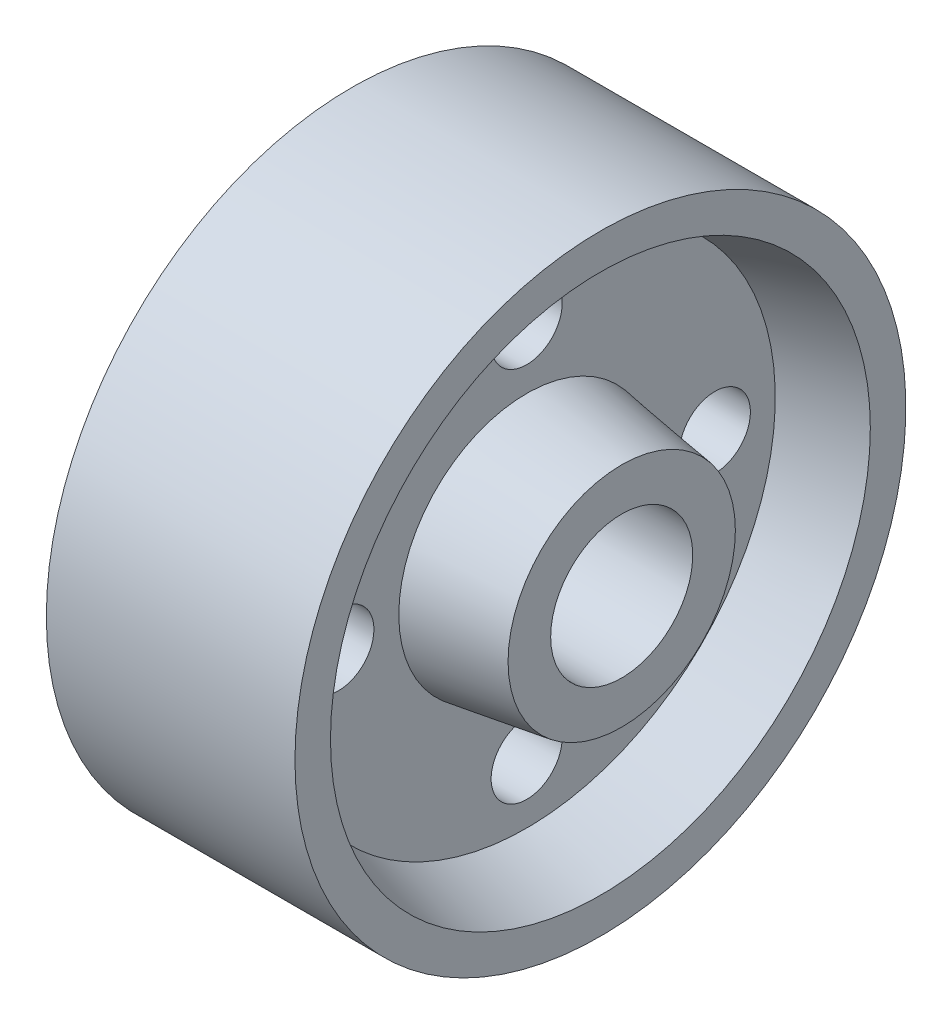
SolidWorks part; units mm, degrees
ref_plane "Front Plane" through (0, 0, 0) normal (0, 0, 1) x (1, 0, 0)
ref_plane "Top Plane" through (0, 0, 0) normal (0, 1, 0) x (1, 0, 0)
ref_plane "Right Plane" through (0, 0, 0) normal (1, 0, 0) x (0, 0, -1)
sketch "Sketch1" plane through (0, 0, 0) normal (0, 0, 1) x (1, 0, 0)
  line L0 (0, 0) -> (94.0781, 0) construction
  line L1 (47.0391, 0) -> (47.0391, 57.6057) construction
  line L2 (67.5391, 10) -> (26.5391, 10)
  line L3 (26.5391, 10) -> (26.5391, 16)
  line L4 (26.5391, 16) -> (39.9221, 18)
  line L5 (39.9221, 18) -> (39.9221, 35)
  line L6 (39.9221, 35) -> (29.5391, 38)
  line L7 (29.5391, 38) -> (29.5391, 43)
  line L8 (29.5391, 43) -> (64.5391, 43)
  line L9 (67.5391, 10) -> (67.5391, 16)
  line L10 (67.5391, 16) -> (54.156, 18)
  line L11 (54.156, 18) -> (54.156, 35)
  line L12 (54.156, 35) -> (64.5391, 38)
  line L13 (64.5391, 38) -> (64.5391, 43)
  point P14 (47.0391, 10)
  point P19 (47.0391, 43)
  dimension "D1" = 20.5
  dimension "D2" = 17.5
  dimension "D3" = 20
  dimension "D4" = 32
  dimension "D5" = 36
  dimension "D6" = 70
  dimension "D7" = 76
  dimension "D8" = 86
  dimension "D9" = 13.383
  dimension "D10" = 57.6057
  dimension "D11" = 94.0781
revolve "Revolve1" add sketch "Sketch1" angle 360 about L0
sketch "Sketch2" plane through (54.156, 0, 0) normal (1, 0, 0) x (0, 0, -1)
  circle A0 centre (0, 0) radius 26.5 construction
  circle A1 centre (0, 26.5) radius 5
  circle A2 centre (26.5, 0) radius 5
  circle A3 centre (0, -26.5) radius 5
  circle A4 centre (-26.5, 0) radius 5
  point P5 (34.0225, -12.0236)
  point P6 (0, 0)
  point P14 (0, 0)
  dimension "D1" = 53
  dimension "D2" = 10
  dimension "D3" = 4
extrude "Cut-Extrude1" cut sketch "Sketch2" against normal blind 25
